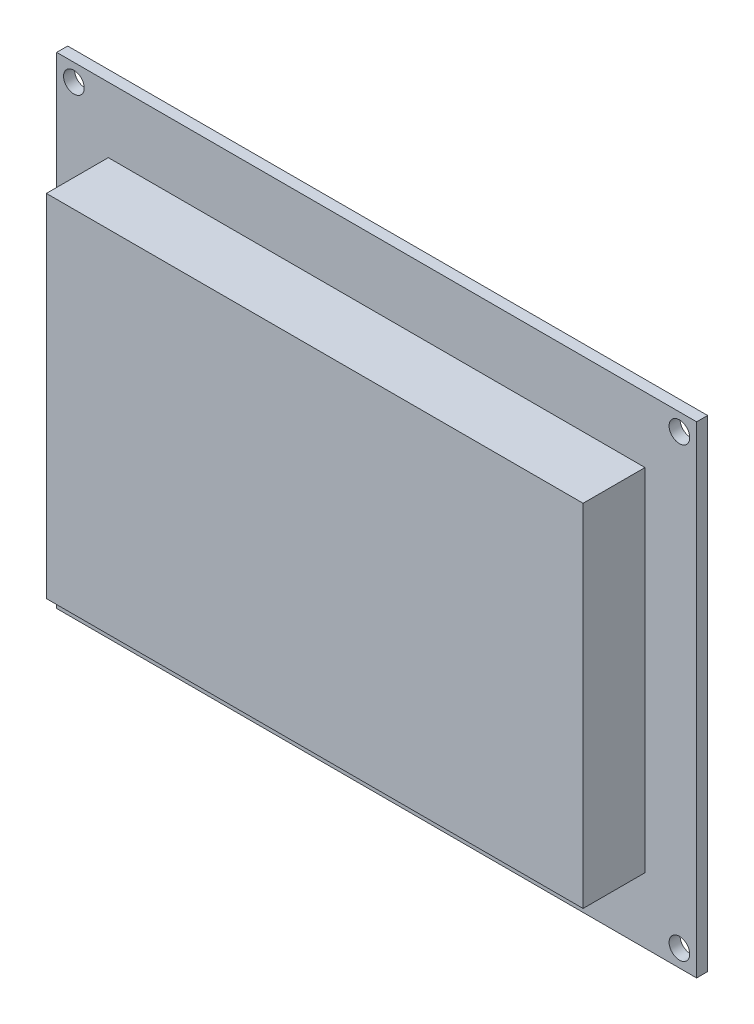
SolidWorks part; units mm, degrees
ref_plane "前视基准面" through (0, 0, 0) normal (0, 0, 1) x (1, 0, 0)
ref_plane "上视基准面" through (0, 0, 0) normal (0, 1, 0) x (1, 0, 0)
ref_plane "右视基准面" through (0, 0, 0) normal (1, 0, 0) x (0, 0, -1)
sketch "草图1" plane through (0, 0, 0) normal (0, 0, 1) x (1, 0, 0)
  line L1 (0, 0) -> (93, 0)
  line L2 (0, 0) -> (0, 70)
  line L3 (0, 70) -> (93, 70)
  line L4 (93, 0) -> (93, 70)
  dimension "D1" = 93
  dimension "D2" = 70
extrude "凸台-拉伸1" add sketch "草图1" along normal blind 1.6
sketch "草图2" plane through (0, 0, 1.6) normal (0, 0, 1) x (1, 0, 0)
  line L0 (93, 70) -> (0, 70) construction
  line L1 (0, 70) -> (0, 0) construction
  line L2 (46.5, 0) -> (46.5, 70) construction
  line L3 (0, 0) -> (93, 0) construction
  line L4 (0, 35) -> (93, 35) construction
  line L5 (93, 0) -> (93, 70) construction
  circle A0 centre (2.5, 67.5) radius 1.5
  circle A1 centre (90.5, 67.5) radius 1.5
  circle A2 centre (90.5, 67.5) radius 1.5
  circle A3 centre (90.5, 2.5) radius 1.5
  circle A4 centre (90.5, 2.5) radius 1.5
  circle A5 centre (2.5, 2.5) radius 1.5
  dimension "D1" = 3
  dimension "D2" = 2.5
  dimension "D3" = 2.5
extrude "切除-拉伸1" cut sketch "草图2" against normal through all contours A5 | A3 | A1 | A0
sketch "草图3" plane through (0, 0, 1.6) normal (0, 0, 1) x (1, 0, 0)
  line L0 (85.5, 60.5) -> (85.5, 9.5)
  line L1 (46.5, 70) -> (46.5, 0) construction
  line L2 (93, 70) -> (0, 70) construction
  line L3 (0, 0) -> (93, 0) construction
  line L4 (7.5, 60.5) -> (85.5, 60.5)
  line L5 (0, 35) -> (93, 35) construction
  line L6 (0, 70) -> (0, 0) construction
  line L7 (93, 0) -> (93, 70) construction
  line L8 (7.5, 9.5) -> (85.5, 9.5)
  line L9 (7.5, 60.5) -> (7.5, 9.5)
  point P17 (85.5, 35)
  point P18 (46.5, 9.5)
  point P19 (46.5, 60.5)
  dimension "D1" = 78
  dimension "D2" = 51
extrude "凸台-拉伸2" add sketch "草图3" along normal blind 9
sketch "草图4" plane through (0, 0, 0) normal (0, 0, -1) x (-1, 0, 0)
  line L0 (-14, 3.6) -> (-14, 1.4)
  line L1 (0, 70) -> (0, 0) construction
  line L2 (-65, 2.5) -> (0, 2.5) construction
  line L4 (0, 0) -> (-93, 0) construction
  line L5 (-65, 3.6) -> (-14, 3.6)
  line L6 (-65, 3.6) -> (-65, 1.4)
  line L7 (-65, 1.4) -> (-14, 1.4)
  dimension "D1" = 14
  dimension "D2" = 2.5
  dimension "D3" = 2.2
  dimension "D4" = 51
extrude "凸台-拉伸3" add sketch "草图4" along normal blind 8
sketch "草图5" plane through (0, 0, -8) normal (0, 0, -1) x (-1, 0, 0)
  line L0 (-39.5, 3.6) -> (-39.5, 1.4) construction
  line L1 (-14, 3.6) -> (-65, 3.6) construction
  line L2 (-65, 1.4) -> (-14, 1.4) construction
  line L3 (-65, 2.5) -> (-14, 2.5) construction
  line L4 (-65, 3.6) -> (-65, 1.4) construction
  line L5 (-14, 1.4) -> (-14, 3.6) construction
  circle A0 centre (-38.23, 2.5) radius 0.4
  circle A1 centre (-40.77, 2.5) radius 0.4
  circle A2 centre (-43.31, 2.5) radius 0.4
  circle A3 centre (-45.85, 2.5) radius 0.4
  circle A4 centre (-48.39, 2.5) radius 0.4
  circle A5 centre (-50.93, 2.5) radius 0.4
  circle A6 centre (-53.47, 2.5) radius 0.4
  circle A7 centre (-56.01, 2.5) radius 0.4
  circle A8 centre (-58.55, 2.5) radius 0.4
  circle A9 centre (-61.09, 2.5) radius 0.4
  circle A10 centre (-63.63, 2.5) radius 0.4
  circle A11 centre (-35.69, 2.5) radius 0.4
  circle A12 centre (-33.15, 2.5) radius 0.4
  circle A13 centre (-30.61, 2.5) radius 0.4
  circle A14 centre (-28.07, 2.5) radius 0.4
  circle A15 centre (-25.53, 2.5) radius 0.4
  circle A16 centre (-22.99, 2.5) radius 0.4
  circle A17 centre (-20.45, 2.5) radius 0.4
  circle A18 centre (-17.91, 2.5) radius 0.4
  circle A19 centre (-15.37, 2.5) radius 0.4
  dimension "D1" = 0.8
  dimension "D2" = 2.54
  dimension "D3" = 11
  dimension "D4" = 10
extrude "凸台-拉伸4" add sketch "草图5" along normal blind 2
